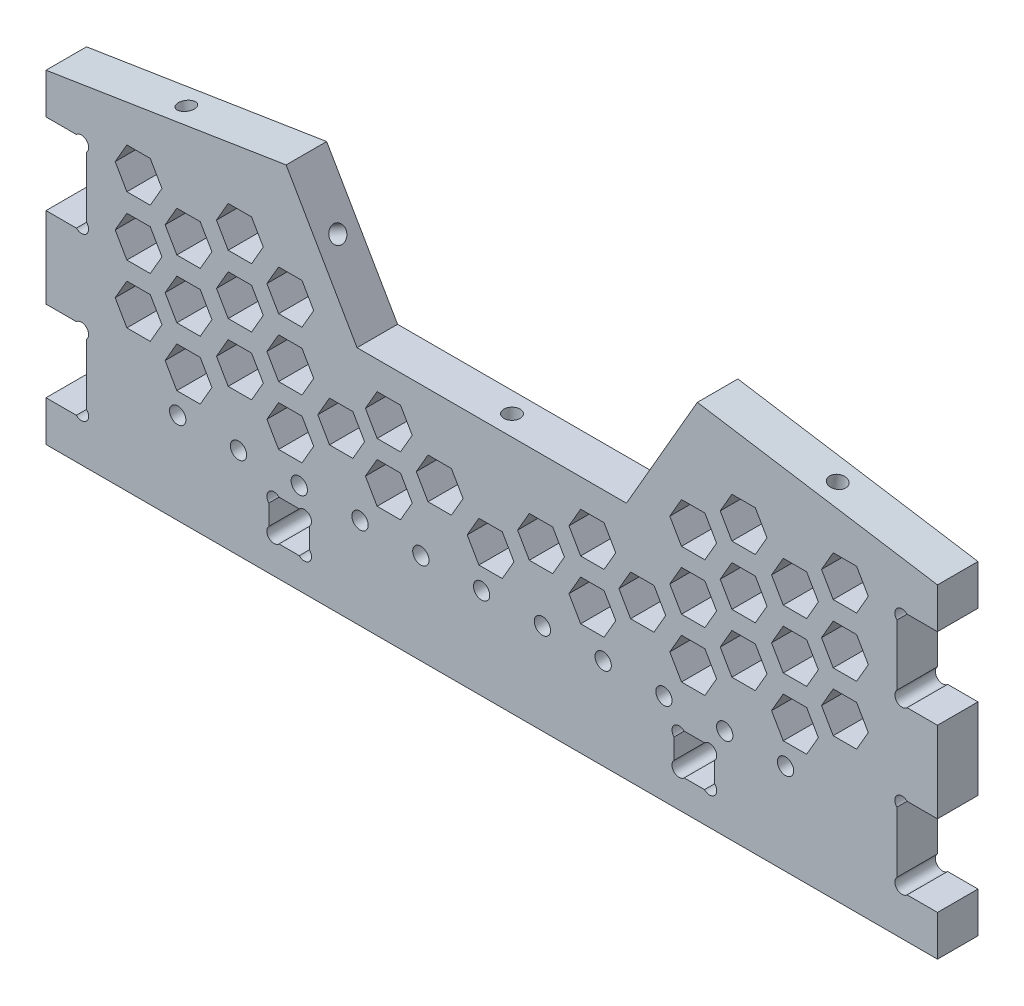
SolidWorks part; units mm, degrees
material "6061 Alloy"
ref_plane "Front" through (0, 0, 0) normal (0, 0, 1) x (1, 0, 0)
ref_plane "Top" through (0, 0, 0) normal (0, 1, 0) x (1, 0, 0)
ref_plane "Right" through (0, 0, 0) normal (1, 0, 0) x (0, 0, -1)
sketch "Sketch2" plane through (0, 0, 0) normal (0, 0, 1) x (1, 0, 0)
  line L1 (-139.7, -50.8) -> (139.7, -50.8)
  line L2 (-139.7, -50.8) -> (-139.7, 50.8)
  line L3 (-139.7, 50.8) -> (139.7, 50.8)
  line L4 (139.7, -50.8) -> (139.7, 50.8)
  line L5 (-139.7, -50.8) -> (139.7, 50.8) construction
  line L6 (-139.7, 50.8) -> (139.7, -50.8) construction
  point P0 (0, 0)
  dimension "D1" = 279.4
  dimension "D2" = 101.6
extrude "Rectangle Extrusion" add sketch "Sketch2" along normal blind 12.7
sketch "Sketch3" plane through (0, 0, 0) normal (0, 0, -1) x (-1, 0, 0)
  line L0 (-139.7, -50.8) -> (-63.5, -50.8) construction
  line L1 (139.7, -50.8) -> (-139.7, -50.8) construction
  line L2 (-63.5, -50.8) -> (-63.5, -34.925) construction
  line L3 (0, 6.985) -> (0, -6.985) construction
  line L4 (-69.85, -41.275) -> (-57.15, -41.275)
  line L5 (-69.85, -41.275) -> (-69.85, -28.575)
  line L6 (-69.85, -28.575) -> (-57.15, -28.575)
  line L7 (-57.15, -41.275) -> (-57.15, -28.575)
  line L8 (-69.85, -41.275) -> (-57.15, -28.575) construction
  line L9 (-69.85, -28.575) -> (-57.15, -41.275) construction
  line L10 (69.85, -28.575) -> (57.15, -28.575)
  line L11 (57.15, -41.275) -> (57.15, -28.575)
  line L12 (69.85, -41.275) -> (57.15, -41.275)
  line L13 (69.85, -41.275) -> (69.85, -28.575)
  line L14 (-69.85, -34.925) -> (-57.15, -34.925) construction
  circle A0 centre (-68.2625, -30.1625) radius 2.2454
  circle A1 centre (-58.7375, -30.1625) radius 2.2454
  circle A2 centre (-58.7375, -39.6875) radius 2.2454
  circle A3 centre (-68.2625, -39.6875) radius 2.2454
  circle A4 centre (58.7375, -39.6875) radius 2.2454
  circle A5 centre (68.2625, -39.6875) radius 2.2454
  circle A6 centre (58.7375, -30.1625) radius 2.2454
  circle A7 centre (68.2625, -30.1625) radius 2.2454
  dimension "D5" = 1.5875
  dimension "D6" = 4.4907
  dimension "D1" = 76.2
  dimension "D2" = 9.525
  dimension "D3" = 12.7
  dimension "D4" = 12.7
extrude "Slotting Holes" cut sketch "Sketch3" against normal up to surface (12.7 mm away) contours L6 A0 L5 | L5 A3 L4 A2 L7 A1 L6 A0 | L5 A0 L6 | A1 L7 L6 | A1 L6 L7 | L7 A2 L4 | L4 A2 L7 | A3 L5 L4 | A3 L4 L5 | L10 A6 L11 | L11 A6 L10 | L13 A7 L10 A6 L11 A4 L12 A5 | A7 L13 L10 | A7 L10 L13 | L12 A5 L13 | A4 L12 L11 | L13 A5 L12 | A4 L11 L12 up to face at (0, 0, 12.7)
sketch "Sketch4" plane through (0, 0, 12.7) normal (0, 0, 1) x (1, 0, 0)
  line L0 (0, -11.43) -> (0, 0) construction
  line L1 (6.9677, 27.5012) -> (3.3015, 33.8512)
  line L2 (-24.9281, 27.5012) -> (-28.5942, 33.8512)
  line L3 (-28.5942, 33.8512) -> (-35.9266, 33.8512)
  line L4 (-35.9266, 33.8512) -> (-39.5928, 27.5012)
  line L5 (-39.5928, 27.5012) -> (-35.9266, 21.1512)
  line L6 (-35.9266, 21.1512) -> (-28.5942, 21.1512)
  line L7 (-28.5942, 21.1512) -> (-24.9281, 27.5012)
  line L8 (3.3015, 33.8512) -> (-4.0309, 33.8512)
  line L9 (-4.0309, 33.8512) -> (-7.697, 27.5012)
  line L10 (-7.697, 27.5012) -> (-4.0309, 21.1512)
  line L11 (-4.0309, 21.1512) -> (3.3015, 21.1512)
  line L12 (3.3015, 21.1512) -> (6.9677, 27.5012)
  line L13 (38.8634, 27.5012) -> (35.1972, 33.8512)
  line L14 (35.1972, 33.8512) -> (27.8648, 33.8512)
  line L15 (27.8648, 33.8512) -> (24.1987, 27.5012)
  line L16 (24.1987, 27.5012) -> (27.8648, 21.1512)
  line L17 (27.8648, 21.1512) -> (35.1972, 21.1512)
  line L18 (35.1972, 21.1512) -> (38.8634, 27.5012)
  line L19 (-8.9802, 18.2937) -> (-12.6464, 24.6437)
  line L20 (-12.6464, 24.6437) -> (-19.9787, 24.6437)
  line L21 (-19.9787, 24.6437) -> (-23.6449, 18.2937)
  line L22 (-23.6449, 18.2937) -> (-19.9787, 11.9437)
  line L23 (-19.9787, 11.9437) -> (-12.6464, 11.9437)
  line L24 (-12.6464, 11.9437) -> (-8.9802, 18.2937)
  line L25 (22.7698, 18.2937) -> (19.1036, 24.6437)
  line L26 (19.1036, 24.6437) -> (11.7713, 24.6437)
  line L27 (11.7713, 24.6437) -> (8.1051, 18.2937)
  line L28 (8.1051, 18.2937) -> (11.7713, 11.9437)
  line L29 (11.7713, 11.9437) -> (19.1036, 11.9437)
  line L30 (19.1036, 11.9437) -> (22.7698, 18.2937)
  line L31 (-24.9281, 9.0862) -> (-28.5942, 15.4362)
  line L32 (-28.5942, 15.4362) -> (-35.9266, 15.4362)
  line L33 (-35.9266, 15.4362) -> (-39.5928, 9.0862)
  line L34 (-39.5928, 9.0862) -> (-35.9266, 2.7362)
  line L35 (-35.9266, 2.7362) -> (-28.5942, 2.7362)
  line L36 (-28.5942, 2.7362) -> (-24.9281, 9.0862)
  line L37 (6.9677, 9.0862) -> (3.3015, 15.4362)
  line L38 (3.3015, 15.4362) -> (-4.0309, 15.4362)
  line L39 (-4.0309, 15.4362) -> (-7.697, 9.0862)
  line L40 (-7.697, 9.0862) -> (-4.0309, 2.7362)
  line L41 (-4.0309, 2.7362) -> (3.3015, 2.7362)
  line L42 (3.3015, 2.7362) -> (6.9677, 9.0862)
  line L43 (38.8634, 9.0862) -> (35.1972, 15.4362)
  line L44 (35.1972, 15.4362) -> (27.8648, 15.4362)
  line L45 (27.8648, 15.4362) -> (24.1987, 9.0862)
  line L46 (24.1987, 9.0862) -> (27.8648, 2.7362)
  line L47 (27.8648, 2.7362) -> (35.1972, 2.7362)
  line L48 (35.1972, 2.7362) -> (38.8634, 9.0862)
  line L49 (-24.9281, -9.3288) -> (-28.5942, -2.9788)
  line L50 (-28.5942, -2.9788) -> (-35.9266, -2.9788)
  line L51 (-35.9266, -2.9788) -> (-39.5928, -9.3288)
  line L52 (-39.5928, -9.3288) -> (-35.9266, -15.6788)
  line L53 (-35.9266, -15.6788) -> (-28.5942, -15.6788)
  line L54 (-28.5942, -15.6788) -> (-24.9281, -9.3288)
  line L55 (-8.9802, -18.5363) -> (-12.6464, -12.1863)
  line L56 (-12.6464, -12.1863) -> (-19.9787, -12.1863)
  line L57 (-19.9787, -12.1863) -> (-23.6449, -18.5363)
  line L58 (-23.6449, -18.5363) -> (-19.9787, -24.8863)
  line L59 (-19.9787, -24.8863) -> (-12.6464, -24.8863)
  line L60 (-12.6464, -24.8863) -> (-8.9802, -18.5363)
  line L61 (6.9677, -9.3288) -> (3.3015, -2.9788)
  line L62 (3.3015, -2.9788) -> (-4.0309, -2.9788)
  line L63 (-4.0309, -2.9788) -> (-7.697, -9.3288)
  line L64 (-7.697, -9.3288) -> (-4.0309, -15.6788)
  line L65 (-4.0309, -15.6788) -> (3.3015, -15.6788)
  line L66 (3.3015, -15.6788) -> (6.9677, -9.3288)
  line L67 (22.7698, -18.5363) -> (19.1036, -12.1863)
  line L68 (19.1036, -12.1863) -> (11.7713, -12.1863)
  line L69 (11.7713, -12.1863) -> (8.1051, -18.5363)
  line L70 (8.1051, -18.5363) -> (11.7713, -24.8863)
  line L71 (11.7713, -24.8863) -> (19.1036, -24.8863)
  line L72 (19.1036, -24.8863) -> (22.7698, -18.5363)
  line L73 (38.8634, -9.3288) -> (35.1972, -2.9788)
  line L74 (35.1972, -2.9788) -> (27.8648, -2.9788)
  line L75 (27.8648, -2.9788) -> (24.1987, -9.3288)
  line L76 (24.1987, -9.3288) -> (27.8648, -15.6788)
  line L77 (27.8648, -15.6788) -> (35.1972, -15.6788)
  line L78 (35.1972, -15.6788) -> (38.8634, -9.3288)
  line L79 (38.8634, -27.7438) -> (35.1972, -21.3938)
  line L80 (35.1972, -21.3938) -> (27.8648, -21.3938)
  line L81 (27.8648, -21.3938) -> (24.1987, -27.7438)
  line L82 (24.1987, -27.7438) -> (27.8648, -34.0938)
  line L83 (27.8648, -34.0938) -> (35.1972, -34.0938)
  line L84 (35.1972, -34.0938) -> (38.8634, -27.7438)
  line L85 (6.9677, -27.7438) -> (3.3015, -21.3938)
  line L86 (-4.0309, -21.3938) -> (-7.697, -27.7438)
  line L87 (-7.697, -27.7438) -> (-4.0309, -34.0938)
  line L88 (-4.0309, -34.0938) -> (3.3015, -34.0938)
  line L89 (3.3015, -34.0938) -> (6.9677, -27.7438)
  line L90 (3.3015, -21.3938) -> (-4.0309, -21.3938)
  line L91 (-24.9281, -27.7438) -> (-28.5942, -21.3938)
  line L92 (-28.5942, -21.3938) -> (-35.9266, -21.3938)
  line L93 (-35.9266, -21.3938) -> (-39.5928, -27.7438)
  line L94 (-39.5928, -27.7438) -> (-35.9266, -34.0938)
  line L95 (-35.9266, -34.0938) -> (-28.5942, -34.0938)
  line L96 (-28.5942, -34.0938) -> (-24.9281, -27.7438)
  line L97 (22.7698, -0.1213) -> (19.1036, 6.2287)
  line L98 (19.1036, 6.2287) -> (11.7713, 6.2287)
  line L99 (11.7713, 6.2287) -> (8.1051, -0.1213)
  line L100 (8.1051, -0.1213) -> (11.7713, -6.4713)
  line L101 (11.7713, -6.4713) -> (19.1036, -6.4713)
  line L102 (19.1036, -6.4713) -> (22.7698, -0.1213)
  line L103 (-8.9802, -0.1213) -> (-12.6464, 6.2287)
  line L104 (-12.6464, 6.2287) -> (-19.9787, 6.2287)
  line L105 (-19.9787, 6.2287) -> (-23.6449, -0.1213)
  line L106 (-23.6449, -0.1213) -> (-19.9787, -6.4713)
  line L107 (-19.9787, -6.4713) -> (-12.6464, -6.4713)
  line L108 (-12.6464, -6.4713) -> (-8.9802, -0.1213)
  line L109 (-8.9802, -37.0783) -> (-12.6464, -30.7283)
  line L110 (-12.6464, -30.7283) -> (-19.9787, -30.7283)
  line L111 (-19.9787, -30.7283) -> (-23.6449, -37.0783)
  line L112 (-23.6449, -37.0783) -> (-19.9787, -43.4283)
  line L113 (-19.9787, -43.4283) -> (-12.6464, -43.4283)
  line L114 (-12.6464, -43.4283) -> (-8.9802, -37.0783)
  line L115 (22.7698, -37.0783) -> (19.1036, -30.7283)
  line L116 (19.1036, -30.7283) -> (11.7713, -30.7283)
  line L117 (11.7713, -30.7283) -> (8.1051, -37.0783)
  line L118 (8.1051, -37.0783) -> (11.7713, -43.4283)
  line L119 (11.7713, -43.4283) -> (19.1036, -43.4283)
  line L120 (19.1036, -43.4283) -> (22.7698, -37.0783)
  line L121 (-8.9802, 36.8357) -> (-12.6464, 43.1857)
  line L122 (-12.6464, 43.1857) -> (-19.9787, 43.1857)
  line L123 (-19.9787, 43.1857) -> (-23.6449, 36.8357)
  line L124 (-23.6449, 36.8357) -> (-19.9787, 30.4857)
  line L125 (-19.9787, 30.4857) -> (-12.6464, 30.4857)
  line L126 (-12.6464, 30.4857) -> (-8.9802, 36.8357)
  line L127 (22.7698, 36.8357) -> (19.1036, 43.1857)
  line L128 (19.1036, 43.1857) -> (11.7713, 43.1857)
  line L129 (11.7713, 43.1857) -> (8.1051, 36.8357)
  line L130 (8.1051, 36.8357) -> (11.7713, 30.4857)
  line L131 (11.7713, 30.4857) -> (19.1036, 30.4857)
  line L132 (19.1036, 30.4857) -> (22.7698, 36.8357)
  line L133 (63.5, -11.43) -> (63.5, 0) construction
  line L134 (70.4677, 27.5012) -> (66.8015, 33.8512)
  line L141 (66.8015, 33.8512) -> (59.4691, 33.8512)
  line L142 (59.4691, 33.8512) -> (55.803, 27.5012)
  line L143 (55.803, 27.5012) -> (59.4691, 21.1512)
  line L144 (59.4691, 21.1512) -> (66.8015, 21.1512)
  line L145 (66.8015, 21.1512) -> (70.4677, 27.5012)
  line L146 (102.3634, 27.5012) -> (98.6972, 33.8512)
  line L147 (98.6972, 33.8512) -> (91.3648, 33.8512)
  line L148 (91.3648, 33.8512) -> (87.6987, 27.5012)
  line L149 (87.6987, 27.5012) -> (91.3648, 21.1512)
  line L150 (91.3648, 21.1512) -> (98.6972, 21.1512)
  line L151 (98.6972, 21.1512) -> (102.3634, 27.5012)
  line L152 (54.5198, 18.2937) -> (50.8536, 24.6437)
  line L153 (50.8536, 24.6437) -> (43.5213, 24.6437)
  line L154 (43.5213, 24.6437) -> (39.8551, 18.2937)
  line L155 (39.8551, 18.2937) -> (43.5213, 11.9437)
  line L156 (43.5213, 11.9437) -> (50.8536, 11.9437)
  line L157 (50.8536, 11.9437) -> (54.5198, 18.2937)
  line L158 (86.2698, 18.2937) -> (82.6036, 24.6437)
  line L159 (82.6036, 24.6437) -> (75.2713, 24.6437)
  line L160 (75.2713, 24.6437) -> (71.6051, 18.2937)
  line L161 (71.6051, 18.2937) -> (75.2713, 11.9437)
  line L162 (75.2713, 11.9437) -> (82.6036, 11.9437)
  line L163 (82.6036, 11.9437) -> (86.2698, 18.2937)
  line L170 (70.4677, 9.0862) -> (66.8015, 15.4362)
  line L171 (66.8015, 15.4362) -> (59.4691, 15.4362)
  line L172 (59.4691, 15.4362) -> (55.803, 9.0862)
  line L173 (55.803, 9.0862) -> (59.4691, 2.7362)
  line L174 (59.4691, 2.7362) -> (66.8015, 2.7362)
  line L175 (66.8015, 2.7362) -> (70.4677, 9.0862)
  line L176 (102.3634, 9.0862) -> (98.6972, 15.4362)
  line L177 (98.6972, 15.4362) -> (91.3648, 15.4362)
  line L178 (91.3648, 15.4362) -> (87.6987, 9.0862)
  line L179 (87.6987, 9.0862) -> (91.3648, 2.7362)
  line L180 (91.3648, 2.7362) -> (98.6972, 2.7362)
  line L181 (98.6972, 2.7362) -> (102.3634, 9.0862)
  line L188 (54.5198, -18.5363) -> (50.8536, -12.1863)
  line L189 (50.8536, -12.1863) -> (43.5213, -12.1863)
  line L190 (43.5213, -12.1863) -> (39.8551, -18.5363)
  line L191 (39.8551, -18.5363) -> (43.5213, -24.8863)
  line L192 (43.5213, -24.8863) -> (50.8536, -24.8863)
  line L193 (50.8536, -24.8863) -> (54.5198, -18.5363)
  line L194 (70.4677, -9.3288) -> (66.8015, -2.9788)
  line L195 (66.8015, -2.9788) -> (59.4691, -2.9788)
  line L196 (59.4691, -2.9788) -> (55.803, -9.3288)
  line L197 (55.803, -9.3288) -> (59.4691, -15.6788)
  line L198 (59.4691, -15.6788) -> (66.8015, -15.6788)
  line L199 (66.8015, -15.6788) -> (70.4677, -9.3288)
  line L200 (86.2698, -18.5363) -> (82.6036, -12.1863)
  line L201 (82.6036, -12.1863) -> (75.2713, -12.1863)
  line L202 (75.2713, -12.1863) -> (71.6051, -18.5363)
  line L203 (71.6051, -18.5363) -> (75.2713, -24.8863)
  line L204 (75.2713, -24.8863) -> (82.6036, -24.8863)
  line L205 (82.6036, -24.8863) -> (86.2698, -18.5363)
  line L206 (102.3634, -9.3288) -> (98.6972, -2.9788)
  line L207 (98.6972, -2.9788) -> (91.3648, -2.9788)
  line L208 (91.3648, -2.9788) -> (87.6987, -9.3288)
  line L209 (87.6987, -9.3288) -> (91.3648, -15.6788)
  line L210 (91.3648, -15.6788) -> (98.6972, -15.6788)
  line L211 (98.6972, -15.6788) -> (102.3634, -9.3288)
  line L212 (102.3634, -27.7438) -> (98.6972, -21.3938)
  line L213 (98.6972, -21.3938) -> (91.3648, -21.3938)
  line L214 (91.3648, -21.3938) -> (87.6987, -27.7438)
  line L215 (87.6987, -27.7438) -> (91.3648, -34.0938)
  line L216 (91.3648, -34.0938) -> (98.6972, -34.0938)
  line L217 (98.6972, -34.0938) -> (102.3634, -27.7438)
  line L230 (86.2698, -0.1213) -> (82.6036, 6.2287)
  line L231 (82.6036, 6.2287) -> (75.2713, 6.2287)
  line L232 (75.2713, 6.2287) -> (71.6051, -0.1213)
  line L233 (71.6051, -0.1213) -> (75.2713, -6.4713)
  line L234 (75.2713, -6.4713) -> (82.6036, -6.4713)
  line L235 (82.6036, -6.4713) -> (86.2698, -0.1213)
  line L236 (54.5198, -0.1213) -> (50.8536, 6.2287)
  line L237 (50.8536, 6.2287) -> (43.5213, 6.2287)
  line L238 (43.5213, 6.2287) -> (39.8551, -0.1213)
  line L239 (39.8551, -0.1213) -> (43.5213, -6.4713)
  line L240 (43.5213, -6.4713) -> (50.8536, -6.4713)
  line L241 (50.8536, -6.4713) -> (54.5198, -0.1213)
  line L254 (54.5198, 36.8357) -> (50.8536, 43.1857)
  line L255 (50.8536, 43.1857) -> (43.5213, 43.1857)
  line L256 (43.5213, 43.1857) -> (39.8551, 36.8357)
  line L257 (39.8551, 36.8357) -> (43.5213, 30.4857)
  line L258 (43.5213, 30.4857) -> (50.8536, 30.4857)
  line L259 (50.8536, 30.4857) -> (54.5198, 36.8357)
  line L260 (86.2698, 36.8357) -> (82.6036, 43.1857)
  line L261 (82.6036, 43.1857) -> (75.2713, 43.1857)
  line L262 (75.2713, 43.1857) -> (71.6051, 36.8357)
  line L263 (71.6051, 36.8357) -> (75.2713, 30.4857)
  line L264 (75.2713, 30.4857) -> (82.6036, 30.4857)
  line L265 (82.6036, 30.4857) -> (86.2698, 36.8357)
  line L266 (118.0198, 36.8357) -> (114.3536, 43.1857)
  line L267 (114.3536, 43.1857) -> (107.0213, 43.1857)
  line L268 (107.0213, 43.1857) -> (103.3551, 36.8357)
  line L269 (103.3551, 36.8357) -> (107.0213, 30.4857)
  line L270 (107.0213, 30.4857) -> (114.3536, 30.4857)
  line L271 (114.3536, 30.4857) -> (118.0198, 36.8357)
  line L272 (118.0198, 18.2937) -> (114.3536, 24.6437)
  line L273 (114.3536, 24.6437) -> (107.0213, 24.6437)
  line L274 (107.0213, 24.6437) -> (103.3551, 18.2937)
  line L275 (103.3551, 18.2937) -> (107.0213, 11.9437)
  line L276 (107.0213, 11.9437) -> (114.3536, 11.9437)
  line L277 (114.3536, 11.9437) -> (118.0198, 18.2937)
  line L278 (118.0198, -0.1213) -> (114.3536, 6.2287)
  line L279 (114.3536, 6.2287) -> (107.0213, 6.2287)
  line L280 (107.0213, 6.2287) -> (103.3551, -0.1213)
  line L281 (103.3551, -0.1213) -> (107.0213, -6.4713)
  line L282 (107.0213, -6.4713) -> (114.3536, -6.4713)
  line L283 (114.3536, -6.4713) -> (118.0198, -0.1213)
  line L284 (118.0198, -18.5363) -> (114.3536, -12.1863)
  line L285 (114.3536, -12.1863) -> (107.0213, -12.1863)
  line L286 (107.0213, -12.1863) -> (103.3551, -18.5363)
  line L287 (103.3551, -18.5363) -> (107.0213, -24.8863)
  line L288 (107.0213, -24.8863) -> (114.3536, -24.8863)
  line L289 (114.3536, -24.8863) -> (118.0198, -18.5363)
  line L290 (117.8959, -37.2022) -> (114.2298, -30.8522)
  line L291 (114.2298, -30.8522) -> (106.8974, -30.8522)
  line L292 (106.8974, -30.8522) -> (103.2312, -37.2022)
  line L293 (103.2312, -37.2022) -> (106.8974, -43.5522)
  line L294 (106.8974, -43.5522) -> (114.2298, -43.5522)
  line L295 (114.2298, -43.5522) -> (117.8959, -37.2022)
  line L296 (0, -6.985) -> (0, 6.985) construction
  line L297 (-63.5, -11.43) -> (-63.5, 0) construction
  line L298 (-114.2298, -43.5522) -> (-117.8959, -37.2022)
  line L299 (-106.8974, -43.5522) -> (-114.2298, -43.5522)
  line L300 (-103.2312, -37.2022) -> (-106.8974, -43.5522)
  line L301 (-106.8974, -30.8522) -> (-103.2312, -37.2022)
  line L302 (-114.2298, -30.8522) -> (-106.8974, -30.8522)
  line L303 (-117.8959, -37.2022) -> (-114.2298, -30.8522)
  line L304 (-114.3536, -24.8863) -> (-118.0198, -18.5363)
  line L305 (-107.0213, -24.8863) -> (-114.3536, -24.8863)
  line L306 (-103.3551, -18.5363) -> (-107.0213, -24.8863)
  line L307 (-107.0213, -12.1863) -> (-103.3551, -18.5363)
  line L308 (-114.3536, -12.1863) -> (-107.0213, -12.1863)
  line L309 (-118.0198, -18.5363) -> (-114.3536, -12.1863)
  line L310 (-114.3536, -6.4713) -> (-118.0198, -0.1213)
  line L311 (-107.0213, -6.4713) -> (-114.3536, -6.4713)
  line L312 (-103.3551, -0.1213) -> (-107.0213, -6.4713)
  line L313 (-107.0213, 6.2287) -> (-103.3551, -0.1213)
  line L314 (-114.3536, 6.2287) -> (-107.0213, 6.2287)
  line L315 (-118.0198, -0.1213) -> (-114.3536, 6.2287)
  line L316 (-114.3536, 11.9437) -> (-118.0198, 18.2937)
  line L317 (-107.0213, 11.9437) -> (-114.3536, 11.9437)
  line L318 (-103.3551, 18.2937) -> (-107.0213, 11.9437)
  line L319 (-107.0213, 24.6437) -> (-103.3551, 18.2937)
  line L320 (-114.3536, 24.6437) -> (-107.0213, 24.6437)
  line L321 (-118.0198, 18.2937) -> (-114.3536, 24.6437)
  line L322 (-114.3536, 30.4857) -> (-118.0198, 36.8357)
  line L323 (-107.0213, 30.4857) -> (-114.3536, 30.4857)
  line L324 (-103.3551, 36.8357) -> (-107.0213, 30.4857)
  line L325 (-107.0213, 43.1857) -> (-103.3551, 36.8357)
  line L326 (-114.3536, 43.1857) -> (-107.0213, 43.1857)
  line L327 (-118.0198, 36.8357) -> (-114.3536, 43.1857)
  line L328 (-82.6036, 30.4857) -> (-86.2698, 36.8357)
  line L329 (-75.2713, 30.4857) -> (-82.6036, 30.4857)
  line L330 (-71.6051, 36.8357) -> (-75.2713, 30.4857)
  line L331 (-75.2713, 43.1857) -> (-71.6051, 36.8357)
  line L332 (-82.6036, 43.1857) -> (-75.2713, 43.1857)
  line L333 (-86.2698, 36.8357) -> (-82.6036, 43.1857)
  line L334 (-50.8536, 30.4857) -> (-54.5198, 36.8357)
  line L335 (-43.5213, 30.4857) -> (-50.8536, 30.4857)
  line L336 (-39.8551, 36.8357) -> (-43.5213, 30.4857)
  line L337 (-43.5213, 43.1857) -> (-39.8551, 36.8357)
  line L338 (-50.8536, 43.1857) -> (-43.5213, 43.1857)
  line L339 (-54.5198, 36.8357) -> (-50.8536, 43.1857)
  line L346 (-50.8536, -6.4713) -> (-54.5198, -0.1213)
  line L347 (-43.5213, -6.4713) -> (-50.8536, -6.4713)
  line L348 (-39.8551, -0.1213) -> (-43.5213, -6.4713)
  line L349 (-43.5213, 6.2287) -> (-39.8551, -0.1213)
  line L350 (-50.8536, 6.2287) -> (-43.5213, 6.2287)
  line L351 (-54.5198, -0.1213) -> (-50.8536, 6.2287)
  line L352 (-82.6036, -6.4713) -> (-86.2698, -0.1213)
  line L353 (-75.2713, -6.4713) -> (-82.6036, -6.4713)
  line L354 (-71.6051, -0.1213) -> (-75.2713, -6.4713)
  line L355 (-75.2713, 6.2287) -> (-71.6051, -0.1213)
  line L356 (-82.6036, 6.2287) -> (-75.2713, 6.2287)
  line L357 (-86.2698, -0.1213) -> (-82.6036, 6.2287)
  line L358 (-98.6972, -34.0938) -> (-102.3634, -27.7438)
  line L359 (-91.3648, -34.0938) -> (-98.6972, -34.0938)
  line L360 (-87.6987, -27.7438) -> (-91.3648, -34.0938)
  line L361 (-91.3648, -21.3938) -> (-87.6987, -27.7438)
  line L362 (-98.6972, -21.3938) -> (-91.3648, -21.3938)
  line L363 (-102.3634, -27.7438) -> (-98.6972, -21.3938)
  line L364 (-98.6972, -15.6788) -> (-102.3634, -9.3288)
  line L365 (-91.3648, -15.6788) -> (-98.6972, -15.6788)
  line L366 (-87.6987, -9.3288) -> (-91.3648, -15.6788)
  line L367 (-91.3648, -2.9788) -> (-87.6987, -9.3288)
  line L368 (-98.6972, -2.9788) -> (-91.3648, -2.9788)
  line L369 (-102.3634, -9.3288) -> (-98.6972, -2.9788)
  line L370 (-82.6036, -24.8863) -> (-86.2698, -18.5363)
  line L371 (-75.2713, -24.8863) -> (-82.6036, -24.8863)
  line L372 (-71.6051, -18.5363) -> (-75.2713, -24.8863)
  line L373 (-75.2713, -12.1863) -> (-71.6051, -18.5363)
  line L374 (-82.6036, -12.1863) -> (-75.2713, -12.1863)
  line L375 (-86.2698, -18.5363) -> (-82.6036, -12.1863)
  line L376 (-66.8015, -15.6788) -> (-70.4677, -9.3288)
  line L377 (-59.4691, -15.6788) -> (-66.8015, -15.6788)
  line L378 (-55.803, -9.3288) -> (-59.4691, -15.6788)
  line L379 (-59.4691, -2.9788) -> (-55.803, -9.3288)
  line L380 (-66.8015, -2.9788) -> (-59.4691, -2.9788)
  line L381 (-70.4677, -9.3288) -> (-66.8015, -2.9788)
  line L382 (-50.8536, -24.8863) -> (-54.5198, -18.5363)
  line L383 (-43.5213, -24.8863) -> (-50.8536, -24.8863)
  line L384 (-39.8551, -18.5363) -> (-43.5213, -24.8863)
  line L385 (-43.5213, -12.1863) -> (-39.8551, -18.5363)
  line L386 (-50.8536, -12.1863) -> (-43.5213, -12.1863)
  line L387 (-54.5198, -18.5363) -> (-50.8536, -12.1863)
  line L388 (-98.6972, 2.7362) -> (-102.3634, 9.0862)
  line L389 (-91.3648, 2.7362) -> (-98.6972, 2.7362)
  line L390 (-87.6987, 9.0862) -> (-91.3648, 2.7362)
  line L391 (-91.3648, 15.4362) -> (-87.6987, 9.0862)
  line L392 (-98.6972, 15.4362) -> (-91.3648, 15.4362)
  line L393 (-102.3634, 9.0862) -> (-98.6972, 15.4362)
  line L394 (-66.8015, 2.7362) -> (-70.4677, 9.0862)
  line L395 (-59.4691, 2.7362) -> (-66.8015, 2.7362)
  line L396 (-55.803, 9.0862) -> (-59.4691, 2.7362)
  line L397 (-59.4691, 15.4362) -> (-55.803, 9.0862)
  line L398 (-66.8015, 15.4362) -> (-59.4691, 15.4362)
  line L399 (-70.4677, 9.0862) -> (-66.8015, 15.4362)
  line L400 (-82.6036, 11.9437) -> (-86.2698, 18.2937)
  line L401 (-75.2713, 11.9437) -> (-82.6036, 11.9437)
  line L402 (-71.6051, 18.2937) -> (-75.2713, 11.9437)
  line L403 (-75.2713, 24.6437) -> (-71.6051, 18.2937)
  line L404 (-82.6036, 24.6437) -> (-75.2713, 24.6437)
  line L405 (-86.2698, 18.2937) -> (-82.6036, 24.6437)
  line L406 (-50.8536, 11.9437) -> (-54.5198, 18.2937)
  line L407 (-43.5213, 11.9437) -> (-50.8536, 11.9437)
  line L408 (-39.8551, 18.2937) -> (-43.5213, 11.9437)
  line L409 (-43.5213, 24.6437) -> (-39.8551, 18.2937)
  line L410 (-50.8536, 24.6437) -> (-43.5213, 24.6437)
  line L411 (-54.5198, 18.2937) -> (-50.8536, 24.6437)
  line L412 (-98.6972, 21.1512) -> (-102.3634, 27.5012)
  line L413 (-91.3648, 21.1512) -> (-98.6972, 21.1512)
  line L414 (-87.6987, 27.5012) -> (-91.3648, 21.1512)
  line L415 (-91.3648, 33.8512) -> (-87.6987, 27.5012)
  line L416 (-98.6972, 33.8512) -> (-91.3648, 33.8512)
  line L417 (-102.3634, 27.5012) -> (-98.6972, 33.8512)
  line L418 (-66.8015, 21.1512) -> (-70.4677, 27.5012)
  line L419 (-59.4691, 21.1512) -> (-66.8015, 21.1512)
  line L420 (-55.803, 27.5012) -> (-59.4691, 21.1512)
  line L421 (-59.4691, 33.8512) -> (-55.803, 27.5012)
  line L422 (-66.8015, 33.8512) -> (-59.4691, 33.8512)
  line L423 (-70.4677, 27.5012) -> (-66.8015, 33.8512)
  circle A0 centre (-32.2604, 27.5012) radius 6.35 construction
  circle A1 centre (-0.3647, 27.5012) radius 6.35 construction
  circle A2 centre (31.531, 27.5012) radius 6.35 construction
  circle A3 centre (-16.3126, 18.2937) radius 6.35 construction
  circle A4 centre (15.4374, 18.2937) radius 6.35 construction
  circle A5 centre (-32.2604, 9.0862) radius 6.35 construction
  circle A6 centre (-0.3647, 9.0862) radius 6.35 construction
  circle A7 centre (31.531, 9.0862) radius 6.35 construction
  circle A8 centre (-32.2604, -9.3288) radius 6.35 construction
  circle A9 centre (-16.3126, -18.5363) radius 6.35 construction
  circle A10 centre (-0.3647, -9.3288) radius 6.35 construction
  circle A11 centre (15.4374, -18.5363) radius 6.35 construction
  circle A12 centre (31.531, -9.3288) radius 6.35 construction
  circle A13 centre (31.531, -27.7438) radius 6.35 construction
  circle A14 centre (-0.3647, -27.7438) radius 6.35 construction
  circle A15 centre (-32.2604, -27.7438) radius 6.35 construction
  circle A16 centre (-16.3126, -0.1213) radius 6.35 construction
  circle A17 centre (15.4374, -0.1213) radius 6.35 construction
  circle A18 centre (-16.3126, -37.0783) radius 6.35 construction
  circle A19 centre (15.4374, -37.0783) radius 6.35 construction
  circle A20 centre (-16.3126, 36.8357) radius 6.35 construction
  circle A21 centre (15.4374, 36.8357) radius 6.35 construction
  circle A23 centre (63.1353, 27.5012) radius 6.35 construction
  circle A24 centre (95.031, 27.5012) radius 6.35 construction
  circle A25 centre (47.1874, 18.2937) radius 6.35 construction
  circle A26 centre (78.9374, 18.2937) radius 6.35 construction
  circle A28 centre (63.1353, 9.0862) radius 6.35 construction
  circle A29 centre (95.031, 9.0862) radius 6.35 construction
  circle A31 centre (47.1874, -18.5363) radius 6.35 construction
  circle A32 centre (63.1353, -9.3288) radius 6.35 construction
  circle A33 centre (78.9374, -18.5363) radius 6.35 construction
  circle A34 centre (95.031, -9.3288) radius 6.35 construction
  circle A35 centre (95.031, -27.7438) radius 6.35 construction
  circle A38 centre (47.1874, -0.1213) radius 6.35 construction
  circle A39 centre (78.9374, -0.1213) radius 6.35 construction
  circle A42 centre (47.1874, 36.8357) radius 6.35 construction
  circle A43 centre (78.9374, 36.8357) radius 6.35 construction
  circle A44 centre (110.6874, 36.8357) radius 6.35 construction
  circle A45 centre (110.6874, 18.2937) radius 6.35 construction
  circle A46 centre (110.6874, -0.1213) radius 6.35 construction
  circle A47 centre (110.6874, -18.5363) radius 6.35 construction
  circle A48 centre (110.6874, -37.0783) radius 6.35 construction
  circle A49 centre (-110.6874, -37.0783) radius 6.35 construction
  circle A50 centre (-110.6874, -18.5363) radius 6.35 construction
  circle A51 centre (-110.6874, -0.1213) radius 6.35 construction
  circle A52 centre (-110.6874, 18.2937) radius 6.35 construction
  circle A53 centre (-110.6874, 36.8357) radius 6.35 construction
  circle A54 centre (-78.9374, 36.8357) radius 6.35 construction
  circle A55 centre (-47.1874, 36.8357) radius 6.35 construction
  circle A57 centre (-78.9374, -0.1213) radius 6.35 construction
  circle A58 centre (-47.1874, -0.1213) radius 6.35 construction
  circle A59 centre (-95.031, -27.7438) radius 6.35 construction
  circle A60 centre (-95.031, -9.3288) radius 6.35 construction
  circle A61 centre (-78.9374, -18.5363) radius 6.35 construction
  circle A62 centre (-63.1353, -9.3288) radius 6.35 construction
  circle A63 centre (-47.1874, -18.5363) radius 6.35 construction
  circle A64 centre (-95.031, 9.0862) radius 6.35 construction
  circle A65 centre (-63.1353, 9.0862) radius 6.35 construction
  circle A66 centre (-78.9374, 18.2937) radius 6.35 construction
  circle A67 centre (-47.1874, 18.2937) radius 6.35 construction
  circle A68 centre (-95.031, 27.5012) radius 6.35 construction
  circle A69 centre (-63.1353, 27.5012) radius 6.35 construction
  dimension "D1" = 11.43
  dimension "D4" = 11.43
  dimension "D5" = 2
  dimension "D2" = 2
  dimension "D3" = 2
extrude "Honeycomb Pocketing" cut sketch "Sketch4" against normal up to surface (12.7 mm away) contours L327 L322 L323 L324 L325 L326 | L333 L328 L329 L330 L331 L332 | L339 L334 L335 L336 L337 L338 | L125 L126 L121 L122 L123 L124 | L131 L132 L127 L128 L129 L130 | L258 L259 L254 L255 L256 L257 | L264 L265 L260 L261 L262 L263 | L270 L271 L266 L267 L268 L269 | L150 L151 L146 L147 L148 L149 | L144 L145 L134 L141 L142 L143 | L17 L18 L13 L14 L15 L16 | L11 L12 L1 L8 L9 L10 | L6 L7 L2 L3 L4 L5 | L423 L418 L419 L420 L421 L422 | L417 L412 L413 L414 L415 L416 | L321 L316 L317 L318 L319 L320 | L405 L400 L401 L402 L403 L404 | L411 L406 L407 L408 L409 L410 | L23 L24 L19 L20 L21 L22 | L29 L30 L25 L26 L27 L28 | L156 L157 L152 L153 L154 L155 | L162 L163 L158 L159 L160 L161 | L276 L277 L272 L273 L274 L275 | L180 L181 L176 L177 L178 L179 | L174 L175 L170 L171 L172 L173 | L47 L48 L43 L44 L45 L46 | L41 L42 L37 L38 L39 L40 | L35 L36 L31 L32 L33 L34 | L399 L394 L395 L396 L397 L398 | L393 L388 L389 L390 L391 L392 | L315 L310 L311 L312 L313 L314 | L357 L352 L353 L354 L355 L356 | L351 L346 L347 L348 L349 L350 | L107 L108 L103 L104 L105 L106 | L101 L102 L97 L98 L99 L100 | L240 L241 L236 L237 L238 L239 | L234 L235 L230 L231 L232 L233 | L282 L283 L278 L279 L280 L281 | L381 L376 L377 L378 L379 L380 | L53 L54 L49 L50 L51 L52 | L369 L364 L365 L366 L367 L368 | L65 L66 L61 L62 L63 L64 | L77 L78 L73 L74 L75 L76 | L198 L199 L194 L195 L196 L197 | L210 L211 L206 L207 L208 L209 up to face at (-63.5, -34.925, 0)
sketch "Sketch5" plane through (0, 0, 12.7) normal (0, 0, 1) x (1, 0, 0)
  line L0 (139.7, 0) -> (139.7, 50.8) construction
  line L1 (139.7, -50.8) -> (139.7, 50.8) construction
  line L2 (139.7, 0) -> (-139.7, 0) construction
  line L4 (139.7, 25.4) -> (139.7, 38.1)
  line L5 (139.7, 38.1) -> (127, 38.1)
  line L6 (127, 25.4) -> (127, 38.1)
  line L8 (127, 25.4) -> (127, 12.7)
  line L9 (127, 12.7) -> (139.7, 12.7)
  line L10 (139.7, 25.4) -> (139.7, 12.7)
  line L11 (-139.7, 50.8) -> (-139.7, -50.8) construction
  line L12 (127, -12.7) -> (139.7, -12.7)
  line L13 (139.7, -25.4) -> (139.7, -12.7)
  line L14 (127, -25.4) -> (139.7, -25.4)
  line L15 (127, -25.4) -> (127, -12.7)
  line L16 (139.7, -38.1) -> (127, -38.1)
  line L17 (127, -25.4) -> (127, -38.1)
  line L18 (139.7, -25.4) -> (127, -25.4)
  line L19 (139.7, -25.4) -> (139.7, -38.1)
  line L20 (0, 50.8) -> (0, -50.8) construction
  line L21 (139.7, 50.8) -> (-139.7, 50.8) construction
  line L22 (-139.7, -50.8) -> (139.7, -50.8) construction
  line L23 (-139.7, -25.4) -> (-139.7, -38.1)
  line L24 (-139.7, -38.1) -> (-127, -38.1)
  line L25 (-127, -25.4) -> (-127, -38.1)
  line L26 (-127, -25.4) -> (-139.7, -25.4)
  line L27 (-139.7, -25.4) -> (-139.7, -12.7)
  line L28 (-127, -12.7) -> (-139.7, -12.7)
  line L29 (-127, -25.4) -> (-127, -12.7)
  line L30 (-139.7, 38.1) -> (-127, 38.1)
  line L31 (-127, 25.4) -> (-127, 38.1)
  line L32 (-139.7, 25.4) -> (-127, 25.4)
  line L33 (-139.7, 25.4) -> (-139.7, 38.1)
  line L34 (-127, 12.7) -> (-139.7, 12.7)
  line L35 (-139.7, 25.4) -> (-139.7, 12.7)
  line L36 (-127, 25.4) -> (-139.7, 25.4)
  line L37 (-127, 25.4) -> (-127, 12.7)
  line L39 (127, 25.4) -> (127, 38.1)
  line L40 (127, 38.1) -> (139.7, 38.1)
  line L41 (139.7, 25.4) -> (139.7, 38.1)
  line L42 (127, 25.4) -> (127.0258, 25.4258) construction
  line L43 (127, 38.1) -> (136.5248, 28.5752) construction
  line L44 (127, 31.75) -> (133.35, 31.75) construction
  line L45 (127, 12.7) -> (139.7, 12.7)
  line L46 (127, 12.7) -> (127, 25.4)
  line L48 (139.7, 12.7) -> (139.7, 25.4)
  line L49 (127, 12.7) -> (130.1752, 15.8752) construction
  line L50 (127, 25.4) -> (127.0258, 25.3742) construction
  line L52 (139.6742, 25.3742) -> (139.7, 25.4) construction
  line L53 (133.35, 19.05) -> (136.5246, 22.2246) construction
  line L54 (130.1752, 22.2248) -> (136.5246, 15.8754) construction
  line L55 (133.35, 31.75) -> (136.5248, 34.9248) construction
  circle A0 centre (128.5875, 36.5125) radius 2.2454
  arc A4 (127.0258, 25.4258) -> (126.9996, 25.4) centre (128.5875, 23.8125) ccw
  circle A7 centre (128.5875, 14.2875) radius 2.2454
  circle A8 centre (-128.5875, 14.2875) radius 2.2454
  circle A9 centre (-128.5875, 36.5125) radius 2.2454
  circle A10 centre (-128.5875, -36.5125) radius 2.2454
  circle A11 centre (-128.5875, -14.2875) radius 2.2454
  circle A12 centre (128.5875, -14.2875) radius 2.2454
  circle A13 centre (128.5875, -36.5125) radius 2.2454
  arc A14 (139.7, 25.4) -> (139.7002, 25.3998) centre (138.1123, 23.8123) cw
  arc A15 (139.6742, 25.3742) -> (139.7002, 25.3998) centre (138.1125, 26.9875) ccw
  arc A16 (127.0258, 25.3742) -> (126.9996, 25.4) centre (128.5875, 26.9875) cw
  dimension "D7" = 4.4907
  dimension "D11" = 4.4907
  dimension "D1" = 12.7
  dimension "D2" = 12.7
  dimension "D3" = 12.7
  dimension "D4" = 12.7
  dimension "D5" = 12.7
  dimension "D6" = 1.5875
  dimension "D8" = 12.7
  dimension "D9" = 12.7
extrude "Cut-Extrude2" cut sketch "Sketch5" against normal blind 12.7
sketch "Sketch6" plane through (0, 0, 12.7) normal (0, 0, 1) x (1, 0, 0)
  circle A0 centre (-98.425, -22.225) radius 2.5527
  circle A1 centre (-79.375, -22.225) radius 2.5527
  circle A2 centre (-60.325, -22.225) radius 2.5527
  circle A3 centre (-41.275, -22.225) radius 2.5527
  circle A4 centre (-22.225, -22.225) radius 2.5527
  circle A5 centre (-3.175, -22.225) radius 2.5527
  circle A6 centre (15.875, -22.225) radius 2.5527
  circle A7 centre (34.925, -22.225) radius 2.5527
  circle A8 centre (53.975, -22.225) radius 2.5527
  circle A9 centre (73.025, -22.225) radius 2.5527
  circle A10 centre (92.075, -22.225) radius 2.5527
  point P2 (-139.7, -50.8)
extrude "Cut-Extrude3" cut sketch "Sketch6" against normal through all
sketch "Sketch7" plane through (0, 0, 12.7) normal (0, 0, 1) x (1, 0, 0)
  line L0 (-139.7, 50.8) -> (-64.4381, 62.7203)
  line L1 (139.7, 50.8) -> (-139.7, 50.8) construction
  line L2 (139.7, 50.8) -> (64.4381, 62.7203)
  line L3 (-64.4381, 62.7203) -> (64.4381, 62.7203)
  line L4 (-139.7, 50.8) -> (139.7, 50.8)
  dimension "D1" = 76.2
  dimension "D2" = 9
  dimension "D3" = 76.2
  dimension "D4" = 9
extrude "Boss-Extrude1" add sketch "Sketch7" against normal up to surface (12.7 mm away) up to face at (-95.8723, -22.225, 0)
sketch "Sketch8" plane through (-11.2677, 71.1417, 0) normal (-0.1564, 0.9877, 0) x (0.9877, 0.1564, 0)
  line L0 (-91.9332, -12.7) -> (-91.9332, 0) construction
  line L1 (-53.8332, -12.7) -> (-130.0332, -12.7) construction
  line L2 (-53.8332, 0) -> (-130.0332, 0) construction
  circle A0 centre (-91.9332, -6.35) radius 2.54
  dimension "D1" = 5.08
extrude "Cut-Extrude4" cut sketch "Sketch8" against normal blind 9.525
mirror "Mirror1" about plane through (0, 0, 0) normal (1, 0, 0) of "Cut-Extrude4"
sketch "Sketch9" plane through (0, 62.7203, 0) normal (0, 1, 0) x (1, 0, 0)
  line L0 (-64.4381, -6.35) -> (-51.7381, -6.35) construction
  line L1 (-64.4381, 0) -> (-64.4381, -12.7) construction
  line L2 (0, -6.985) -> (0, 6.985) construction
  circle A0 centre (-51.7381, -6.35) radius 2.54
  circle A1 centre (51.7381, -6.35) radius 2.54
  dimension "D2" = 5.08
  dimension "D1" = 12.7
extrude "Cut-Extrude5" cut sketch "Sketch9" against normal blind 9.525
sketch "Sketch10" plane through (0, 0, 12.7) normal (0, 0, 1) x (1, 0, 0)
  line L0 (-64.4381, 62.7203) -> (-42.2131, 24.2255)
  line L1 (64.4381, 62.7203) -> (-64.4381, 62.7203) construction
  line L2 (0, 62.7203) -> (0, -50.8) construction
  line L3 (-139.7, -50.8) -> (139.7, -50.8) construction
  line L4 (64.4381, 62.7203) -> (42.2131, 24.2255)
  line L5 (-42.2131, 24.2255) -> (42.2131, 24.2255)
  line L6 (-64.4381, 62.7203) -> (64.4381, 62.7203)
  dimension "D1" = 60
  dimension "D2" = 44.45
extrude "Cut-Extrude6" cut sketch "Sketch10" against normal through all
sketch "Sketch11" plane through (0, 0, 12.7) normal (0, 0, 1) x (1, 0, 0)
  line L0 (-52.0067, 41.1884) -> (-42.2131, 24.2255)
  line L1 (-42.2131, 24.2255) -> (42.2131, 24.2255)
  line L2 (42.2131, 24.2255) -> (52.0067, 41.1884)
  line L3 (-52.0067, 41.1884) -> (-56.9872, 36.208)
  line L4 (-56.9872, 36.208) -> (-52.0067, 27.2622)
  line L5 (-52.0067, 27.2622) -> (-56.9872, 16.8063)
  line L6 (-56.9872, 16.8063) -> (-52.3349, 8.45)
  line L7 (-52.3349, 8.45) -> (-42.2131, 8.45)
  line L8 (-42.2131, 8.45) -> (-36.7142, 16.8063)
  line L9 (-36.7142, 16.8063) -> (-25.5321, 16.8063)
  line L10 (-25.5321, 16.8063) -> (-20.8798, 8.45)
  line L11 (-20.8798, 8.45) -> (-11.4456, 8.45)
  line L15 (11.5872, 8.45) -> (21.8101, 8.45)
  line L16 (21.8101, 8.45) -> (26.2842, 17.8429)
  line L17 (26.2842, 17.8429) -> (36.0418, 17.8429)
  line L18 (36.0418, 17.8429) -> (45.4347, 8.45)
  line L19 (45.4347, 8.45) -> (53.1779, 8.45)
  line L20 (53.1779, 8.45) -> (58.0429, 18.6635)
  line L21 (58.0429, 18.6635) -> (53.0784, 27.2622)
  line L22 (53.0784, 27.2622) -> (60.604, 38.6982)
  line L23 (60.604, 38.6982) -> (52.0067, 41.1884)
  line L24 (-11.4456, 8.45) -> (-4.564, -0.8749)
  line L25 (-4.564, -0.8749) -> (5.6905, -0.8749)
  line L26 (5.6905, -0.8749) -> (11.5872, 8.45)
extrude "Boss-Extrude2" add sketch "Sketch11" against normal up to surface (12.7 mm away)
sketch "Sketch12" plane through (-21.1699, -12.2225, 0) normal (0.866, 0.5, 0) x (0, 0, -1)
  line L0 (-6.35, 42.0865) -> (-6.35, 86.5365) construction
  line L1 (0, 42.0865) -> (-12.7, 42.0865) construction
  line L2 (0, 86.5365) -> (-12.7, 86.5365) construction
  circle A1 centre (-6.35, 66.8515) radius 2.54
  dimension "D1" = 19.685
  dimension "D2" = 5.08
extrude "Cut-Extrude7" cut sketch "Sketch12" against normal blind 9.525
mirror "Mirror2" about plane through (0, 0, 0) normal (1, 0, 0) of "Cut-Extrude7"
sketch "Sketch13" plane through (0, 24.2255, 0) normal (0, 1, 0) x (1, 0, 0)
  line L0 (-42.2131, -6.35) -> (42.2131, -6.35) construction
  line L1 (-42.2131, 0) -> (-42.2131, -12.7) construction
  line L2 (42.2131, 0) -> (42.2131, -12.7) construction
  circle A0 centre (0, -6.35) radius 2.54
  dimension "D1" = 5.08
extrude "Cut-Extrude8" cut sketch "Sketch13" against normal blind 9.525
